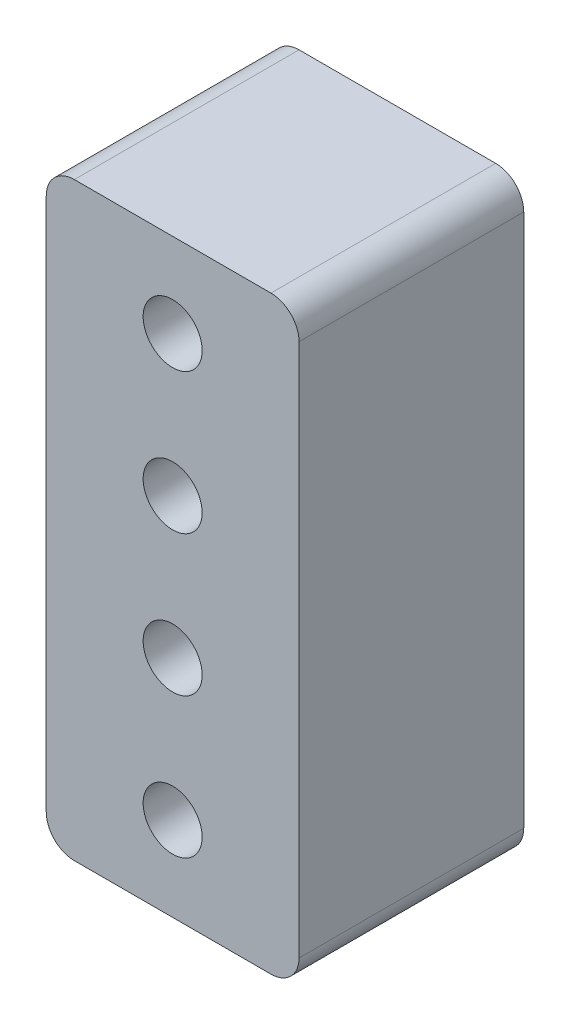
SolidWorks part; units mm, degrees
ref_plane "Front Plane" through (0, 0, 0) normal (0, 0, 1) x (1, 0, 0)
ref_plane "Top Plane" through (0, 0, 0) normal (0, 1, 0) x (1, 0, 0)
ref_plane "Right Plane" through (0, 0, 0) normal (1, 0, 0) x (0, 0, -1)
sketch "Sketch1" plane through (0, 0, 0) normal (0, 0, 1) x (1, 0, 0)
  line L1 (0, 0) -> (45, 0)
  line L2 (0, 0) -> (0, 105)
  line L3 (0, 105) -> (45, 105)
  line L4 (45, 0) -> (45, 105)
  dimension "D1" = 105
  dimension "D2" = 45
extrude "Boss-Extrude1" add sketch "Sketch1" along normal blind 40
sketch "Sketch2" plane through (0, 0, 40) normal (0, 0, 1) x (1, 0, 0)
  line L0 (45, 105) -> (0, 105) construction
  circle A0 centre (22.5, 90) radius 5.25
  point P4 (22.5, 105)
  dimension "D1" = 10.5
  dimension "D2" = 15
extrude "Cut-Extrude1" cut sketch "Sketch2" against normal blind 17.5
sketch "Sketch6" plane through (0, 0, 22.5) normal (0, 0, 1) x (1, 0, 0)
  circle A0 centre (22.5, 90) radius 5.25
ref_plane "Plane4" through (0, 0, 7.5) normal (0, 0, 1) x (1, 0, 0)
sketch "Sketch7" plane through (0, 0, 7.5) normal (0, 0, 1) x (1, 0, 0)
  circle A0 centre (22.5, 90) radius 2.5
  dimension "D1" = 5
loft "Cut-Loft1" cut profiles "Sketch7", "Sketch6"
sketch "Sketch8" plane through (0, 0, 7.5) normal (0, 0, 1) x (1, 0, 0)
  line L0 (22.5, 105) -> (22.5, 162.6816) construction
  line L1 (45, 105) -> (0, 105) construction
  line L2 (22.5, 92.5) -> (22.5, 87.5)
  arc A0 (22.5, 92.5) -> (22.5, 87.5) centre (22.5, 90) ccw
  dimension "D1" = 5
  dimension "D2" = 15
revolve "Cut-Revolve1" cut sketch "Sketch8" angle 360 about L0
pattern_linear "LPattern1" count 4 spacing 25 along (0, -1, 0) of "Cut-Loft1", "Cut-Revolve1", "Cut-Extrude1"
fillet "Fillet1" radius 5 4 edges at (45, 0, 20) (0, 0, 20) (45, 105, 20) (0, 105, 20)
